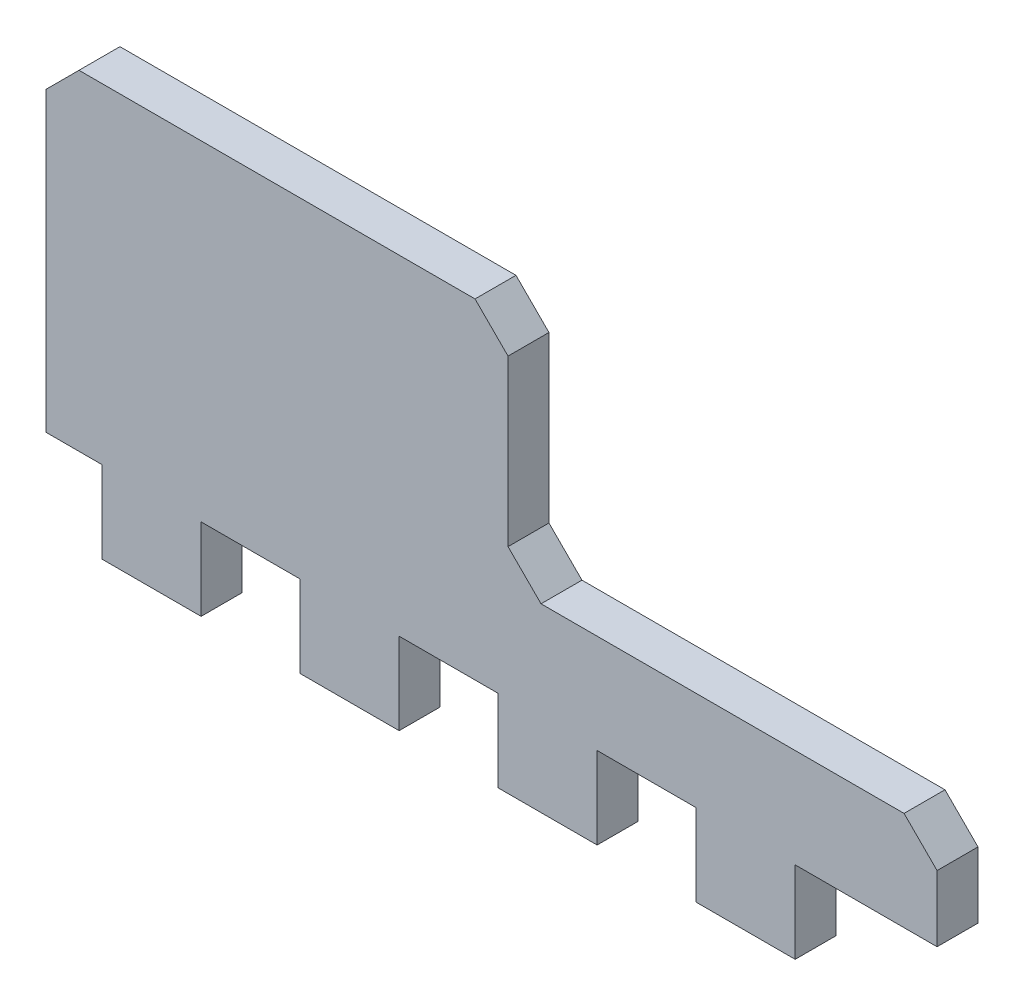
SolidWorks part; units mm, degrees
ref_plane "Front Plane" through (0, 0, 0) normal (0, 0, 1) x (1, 0, 0)
ref_plane "Top Plane" through (0, 0, 0) normal (0, 1, 0) x (1, 0, 0)
ref_plane "Right Plane" through (0, 0, 0) normal (1, 0, 0) x (0, 0, -1)
sketch "Model" plane through (0, 0, 0) normal (0, 0, 1) x (1, 0, 0)
  line L0 (270, 5) -> (0, 5) construction
  line L1 (0, 0) -> (17, 0)
  line L2 (0, 0) -> (0, 90)
  line L3 (150, 30) -> (260, 30)
  line L4 (270, 0) -> (270, 20)
  line L5 (10, 100) -> (0, 90)
  line L6 (270, 20) -> (260, 30)
  line L7 (10, 100) -> (130, 100)
  line L8 (140, 40) -> (140, 90)
  line L9 (107, 0) -> (137, 0)
  line L10 (137, 0) -> (137, -24.8)
  line L11 (77, 0) -> (77, -24.8)
  line L12 (77, -24.8) -> (107, -24.8)
  line L13 (107, 0) -> (107, -24.8)
  line L14 (137, -24.8) -> (167, -24.8)
  line L15 (167, 0) -> (167, -24.8)
  line L16 (167, 0) -> (197, 0)
  line L17 (17, 0) -> (17, -24.8)
  line L18 (17, -24.8) -> (47, -24.8)
  line L19 (47, 0) -> (47, -24.8)
  line L20 (47, 0) -> (77, 0)
  line L21 (140, 90) -> (130, 100)
  line L22 (140, 40) -> (150, 30)
  line L23 (197, 0) -> (197, -24.8)
  line L24 (197, -24.8) -> (227, -24.8)
  line L25 (227, 0) -> (227, -24.8)
  line L26 (227, 0) -> (270, 0)
  point P23 (92, -24.8)
  point P33 (32, -24.8)
  dimension "D14" = 130
  dimension "D16" = 30
  dimension "D17" = 24.8
  dimension "D24" = 10
  dimension "D10" = 270
  dimension "D6" = 100
  dimension "D11" = 30
  dimension "D3" = 17
  dimension "D4" = 10
  dimension "D5" = 135
  dimension "D7" = 10
  dimension "D8" = 135
  dimension "D12" = 10
  dimension "D13" = 135
  dimension "D15" = 10
  dimension "D9" = 30
  dimension "D19" = 3
  dimension "D20" = 2
extrude "Boss-Extrude1" add sketch "Model" along normal blind 12.4
equation "\"tab-width-small\"= 20mm ' Width of the small version of the Tab"
equation "\"tab-width-large\"= 30mm ' Width of the large version of the Tab"
equation "\"material-thickness\"= 12.4mm"
equation "\"D17@Model\"=\"material-thickness\"*2"
equation "\"D1@Boss-Extrude1\" = \"material-thickness\""
equation "\"D16@Model\"=\"tab-width-large\""
